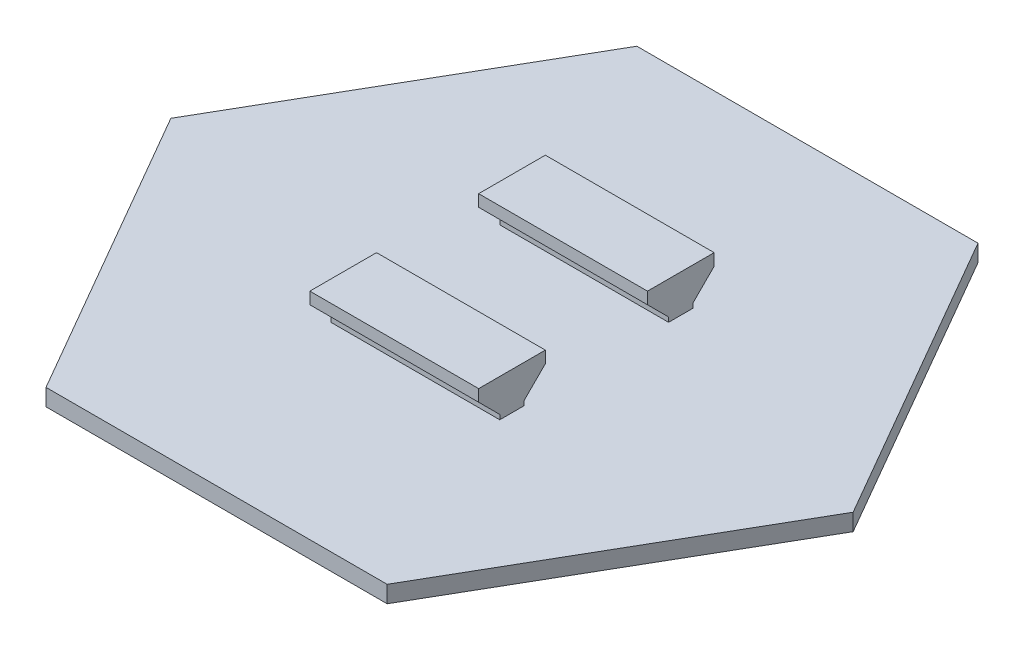
SolidWorks part; units mm, degrees
ref_plane "Front Plane" through (0, 0, 0) normal (0, 0, 1) x (1, 0, 0)
ref_plane "Top Plane" through (0, 0, 0) normal (0, 1, 0) x (1, 0, 0)
ref_plane "Right Plane" through (0, 0, 0) normal (1, 0, 0) x (0, 0, -1)
sketch "Sketch1" plane through (0, 0, 0) normal (0, 1, 0) x (1, 0, 0)
  line L1 (40.4145, 0) -> (20.2073, 35)
  line L2 (20.2073, 35) -> (-20.2073, 35)
  line L3 (-20.2073, 35) -> (-40.4145, 0)
  line L4 (-40.4145, 0) -> (-20.2073, -35)
  line L5 (-20.2073, -35) -> (20.2073, -35)
  line L6 (20.2073, -35) -> (40.4145, 0)
  circle A0 centre (0, 0) radius 35 construction
  point P1 (0, 35)
  dimension "D1" = 70
extrude "Boss-Extrude1" add sketch "Sketch1" along normal mid plane 2
sketch "Sketch2" plane through (0, 0, 0) normal (1, 0, 0) x (0, 0, -1)
  line L0 (-35, 1) -> (0, 1) construction
  line L1 (-11.45, 1) -> (-8.55, 1)
  line L2 (-11.45, 1) -> (-11.45, 1.55)
  line L3 (-11.45, 1.55) -> (-8.55, 1.55)
  line L4 (-8.55, 1) -> (-8.55, 1.55)
  line L5 (-11.45, 1.55) -> (-13.95, 4.05)
  line L6 (-13.95, 4.05) -> (-13.95, 5.45)
  line L7 (-6.05, 4.05) -> (-8.55, 1.55)
  line L8 (-13.95, 5.45) -> (-6.05, 5.45)
  line L9 (-6.05, 5.45) -> (-6.05, 4.05)
  line L10 (0, 1) -> (0, -1) construction
  line L11 (0, 55) -> (0, -55) construction
  line L12 (11.45, 1.55) -> (8.55, 1.55)
  line L13 (11.45, 1) -> (11.45, 1.55)
  line L14 (11.45, 1.55) -> (13.95, 4.05)
  line L15 (13.95, 4.05) -> (13.95, 5.45)
  line L16 (13.95, 5.45) -> (6.05, 5.45)
  line L17 (6.05, 5.45) -> (6.05, 4.05)
  line L18 (6.05, 4.05) -> (8.55, 1.55)
  line L19 (8.55, 1) -> (8.55, 1.55)
  line L20 (11.45, 1) -> (8.55, 1)
  point P6 (-10, 5.45)
  point P11 (-10, 1)
  dimension "D1" = 2.9
  dimension "D2" = 6.05
  dimension "D3" = 0.55
  dimension "D4" = 3.05
  dimension "D5" = 7.9
  dimension "D6" = 1.4
extrude "Boss-Extrude2" add sketch "Sketch2" against normal mid plane 20 contours L17 L18 L12 L14 L15 L16 | L9 L8 L6 L5 L3 L7 | L1 L4 L3 L2 | L20 L13 L12 L19
